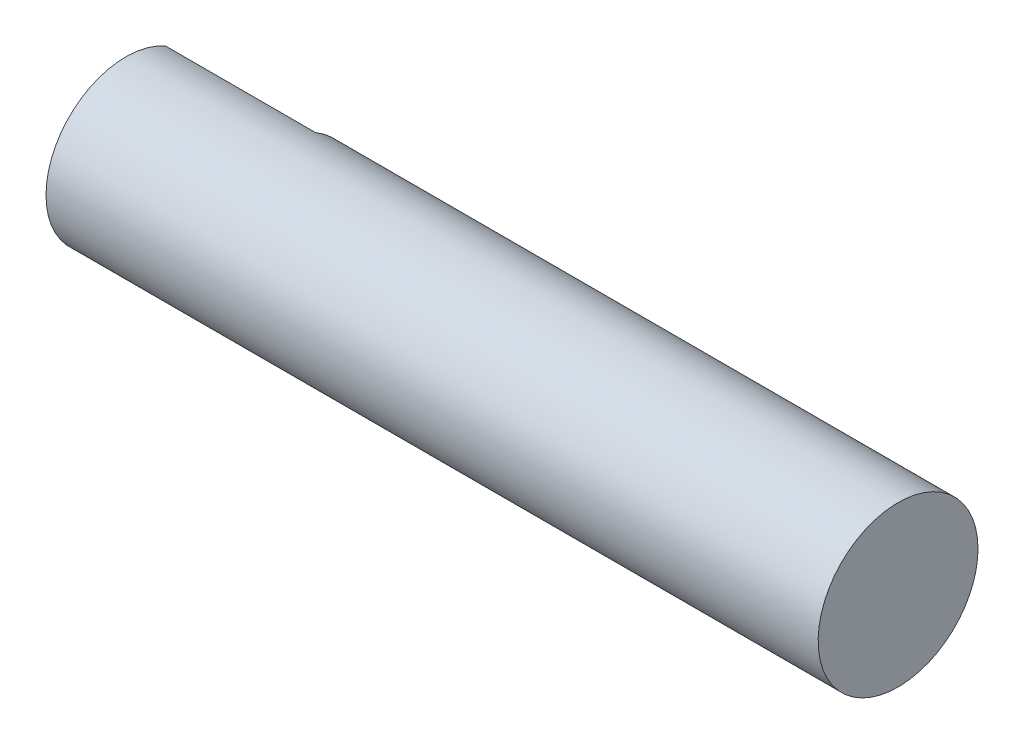
SolidWorks part; units mm, degrees
ref_plane "Front Plane" through (0, 0, 0) normal (0, 0, 1) x (1, 0, 0)
ref_plane "Top Plane" through (0, 0, 0) normal (0, 1, 0) x (1, 0, 0)
ref_plane "Right Plane" through (0, 0, 0) normal (1, 0, 0) x (0, 0, -1)
sketch "Sketch1" plane through (0, 0, 0) normal (1, 0, 0) x (0, 0, -1)
  line L0 (1.985, 3.467) -> (1.985, -3.467)
  line L1 (-3.995, -8) -> (1.985, -8) construction
  line L2 (-3.995, -8) -> (-3.995, 0) construction
  line L4 (1.985, -8) -> (1.985, 3.467) construction
  arc A0 (1.985, 3.467) -> (1.985, -3.467) centre (0, 0) ccw
  dimension "D1" = 7.99
  dimension "D2" = 5.98
  dimension "D3" = 8
extrude "Boss-Extrude1" add sketch "Sketch1" along normal blind 7.5
sketch "Sketch2" plane through (7.5, 0, 0) normal (1, 0, 0) x (0, 0, -1)
  circle A0 centre (0, 0) radius 3.995
  dimension "D1" = 7.99
extrude "Boss-Extrude2" add sketch "Sketch2" along normal blind 31.1
